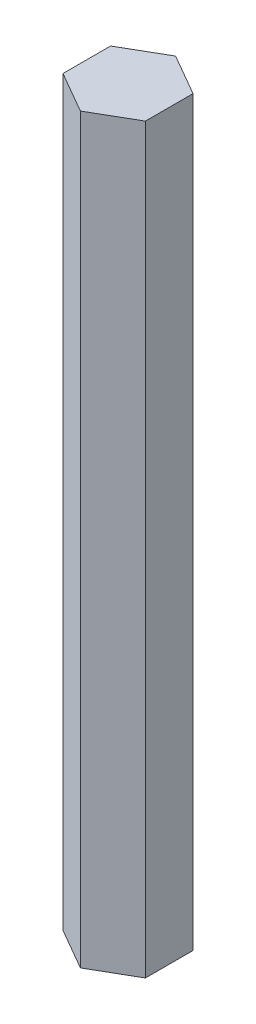
SolidWorks part; units mm, degrees
ref_plane "정면" through (0, 0, 0) normal (0, 0, 1) x (1, 0, 0)
ref_plane "윗면" through (0, 0, 0) normal (0, 1, 0) x (1, 0, 0)
ref_plane "우측면" through (0, 0, 0) normal (1, 0, 0) x (0, 0, -1)
sketch "스케치1" plane through (0, 0, 0) normal (0, 1, 0) x (1, 0, 0)
  line L1 (0, -3.4641) -> (3, -1.7321)
  line L2 (3, -1.7321) -> (3, 1.7321)
  line L3 (3, 1.7321) -> (0, 3.4641)
  line L4 (0, 3.4641) -> (-3, 1.7321)
  line L5 (-3, 1.7321) -> (-3, -1.7321)
  line L6 (-3, -1.7321) -> (0, -3.4641)
  circle A0 centre (0, 0) radius 3 construction
extrude "보스-돌출1" add sketch "스케치1" along normal blind 54
